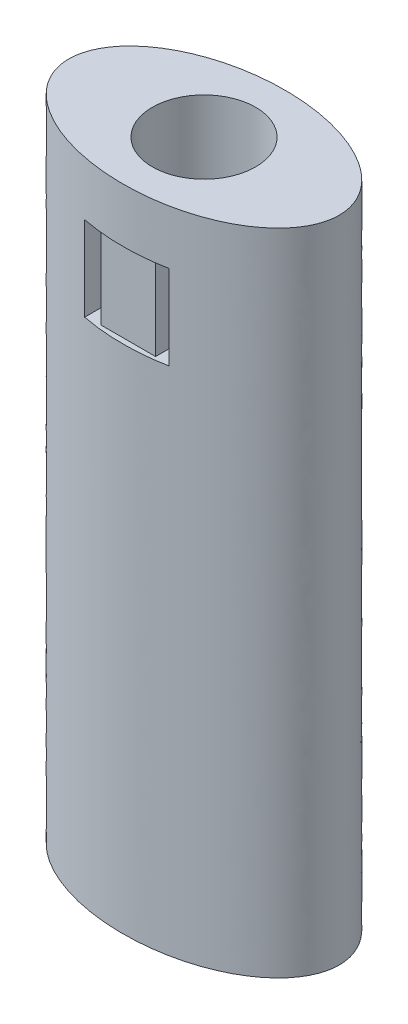
SolidWorks part; units mm, degrees
ref_plane "前视基准面" through (0, 0, 0) normal (0, 0, 1) x (1, 0, 0)
ref_plane "上视基准面" through (0, 0, 0) normal (0, 1, 0) x (1, 0, 0)
ref_plane "右视基准面" through (0, 0, 0) normal (1, 0, 0) x (0, 0, -1)
other "Configuration Table"
sketch "草图1" plane through (0, 0, 0) normal (0, 1, 0) x (1, 0, 0)
  line L0 (-25, 0) -> (25, 0) construction
  ellipse E0 centre (0, 0) end of major axis (25, 0) minor radius 15
  dimension "D1" = 50
  dimension "D2" = 30
extrude "凸台-拉伸1" add sketch "草图1" along normal blind 120
sketch "草图2" plane through (0, 0, 0) normal (0, -1, 0) x (1, 0, 0)
  circle A0 centre (0, 0) radius 9.55
  dimension "D1" = 19.1
extrude "切除-拉伸1" cut sketch "草图2" against normal blind 120
sketch "草图3" plane through (0, 0, 0) normal (0, 0, 1) x (1, 0, 0)
  line L0 (9.55, 120) -> (-9.55, 120) construction
  line L1 (-7.8, 94.4) -> (7.8, 94.4)
  line L2 (-7.8, 94.4) -> (-7.8, 110)
  line L3 (-7.8, 110) -> (7.8, 110)
  line L4 (7.8, 94.4) -> (7.8, 110)
  line L5 (-7.8, 94.4) -> (7.8, 110) construction
  line L6 (-7.8, 110) -> (7.8, 94.4) construction
  point P0 (0, 102.2)
  point P5 (0, 0)
  dimension "D1" = 15.6
  dimension "D2" = 15.6
  dimension "D3" = 10
extrude "切除-拉伸3" cut sketch "草图3" against normal blind 1 from offset 15
sketch "草图4" plane through (0, 0, 14) normal (0, 0, 1) x (1, 0, 0)
  line L0 (-5.05, 110) -> (-7.8, 110) construction
  line L2 (-5.05, 110) -> (-5.05, 94.4)
  line L4 (7.8, 94.4) -> (7.8, 110)
  line L5 (7.8, 110) -> (-7.8, 110)
  line L6 (-7.8, 110) -> (-7.8, 94.4)
  line L7 (-7.8, 94.4) -> (7.8, 94.4)
  line L8 (7.8, 94.4) -> (7.8, 110) construction
  line L9 (7.8, 110) -> (5.05, 110) construction
  line L10 (-7.8, 110) -> (-7.8, 94.4) construction
  line L11 (-7.8, 94.4) -> (-5.05, 94.4) construction
  line L12 (5.05, 110) -> (5.05, 94.4)
  line L13 (-7.8, 110) -> (-5.05, 110)
  line L14 (-7.8, 110) -> (-7.8, 94.4)
  line L15 (-7.8, 94.4) -> (-5.05, 94.4)
  line L16 (7.8, 110) -> (7.8, 94.4)
  line L17 (5.05, 110) -> (7.8, 110)
  line L18 (5.05, 94.4) -> (7.8, 94.4) construction
  line L19 (5.05, 94.4) -> (7.8, 94.4)
  dimension "D2" = 10.1
  dimension "D1" = 0
extrude "切除-拉伸4" cut sketch "草图4" against normal blind 3
